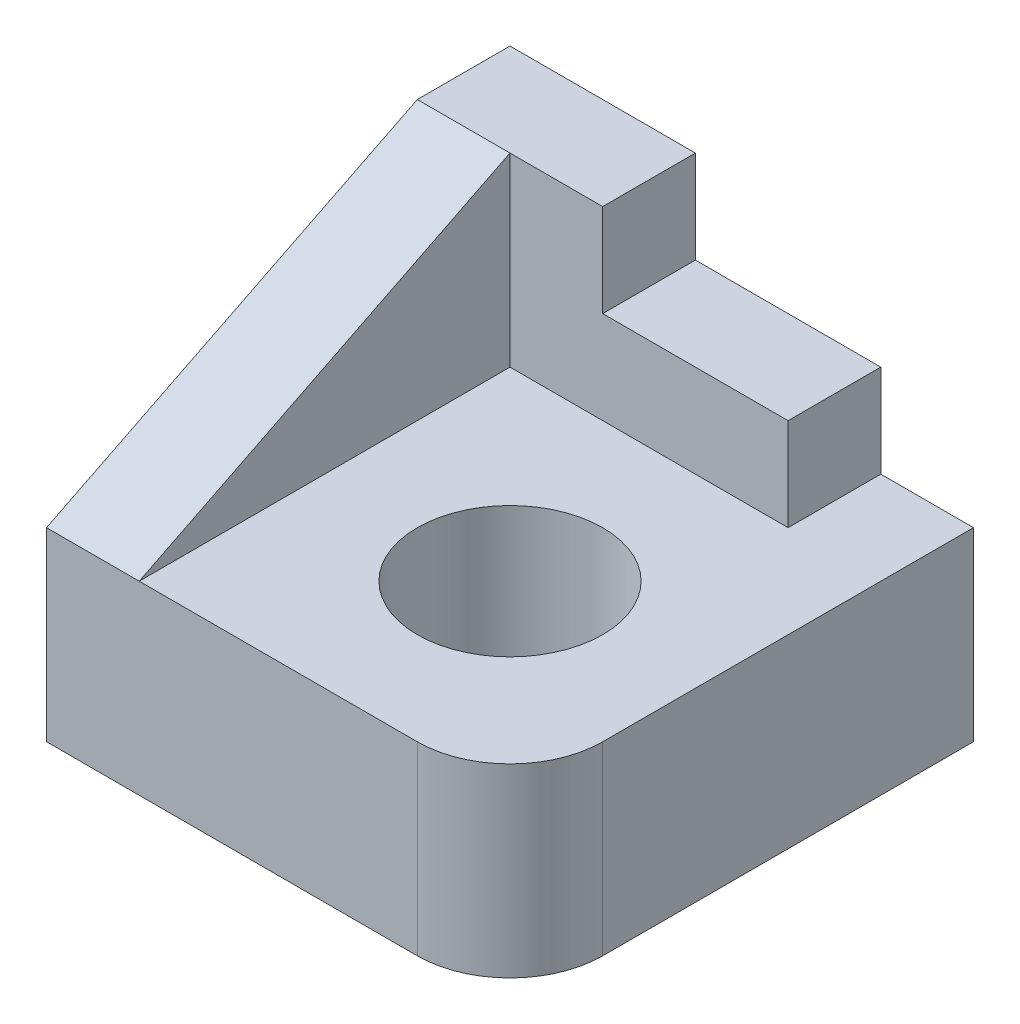
SolidWorks part; units mm, degrees
ref_plane "前基準面" through (0, 0, 0) normal (0, 0, 1) x (1, 0, 0)
ref_plane "上基準面" through (0, 0, 0) normal (0, 1, 0) x (1, 0, 0)
ref_plane "右基準面" through (0, 0, 0) normal (1, 0, 0) x (0, 0, -1)
sketch "草圖1" plane through (0, 0, 0) normal (0, 1, 0) x (1, 0, 0)
  line L1 (0, 0) -> (25, 0)
  line L2 (0, 0) -> (0, -25)
  line L3 (0, -25) -> (20, -25)
  line L4 (25, 0) -> (25, -20)
  arc A0 (25, -20) -> (20, -25) centre (20, -20) cw
  circle A1 centre (15, -15) radius 5
  dimension "D1" = 5
  dimension "D6" = 10
  dimension "D2" = 25
  dimension "D3" = 25
  dimension "D4" = 10
  dimension "D5" = 10
extrude "填料-伸長1" add sketch "草圖1" along normal blind 10
sketch "草圖2" plane through (0, 0, 0) normal (0, 0, -1) x (-1, 0, 0)
  line L1 (0, 10) -> (-10, 10)
  line L2 (0, 10) -> (0, 20)
  line L3 (0, 20) -> (-10, 20)
  line L4 (-10, 10) -> (-10, 20)
  line L5 (-10, 10) -> (-20, 10)
  line L6 (-10, 10) -> (-10, 15)
  line L7 (-10, 15) -> (-20, 15)
  line L8 (-20, 10) -> (-20, 15)
  line M7 (0, 10) -> (-25, 10)
  dimension "D1" = 10
  dimension "D2" = 5
  dimension "D3" = 10
  dimension "D4" = 10
extrude "填料-伸長2" add sketch "草圖2" against normal blind 5 contours L4 L2 L3 M7 | L8 L4 L7 M7
sketch "草圖3" plane through (0, 0, 0) normal (-1, 0, 0) x (0, 0, 1)
  line L0 (5, 20) -> (5, 10)
  line L1 (5, 10) -> (25, 10)
  line L2 (25, 10) -> (5, 20)
extrude "填料-伸長3" add sketch "草圖3" against normal blind 5
